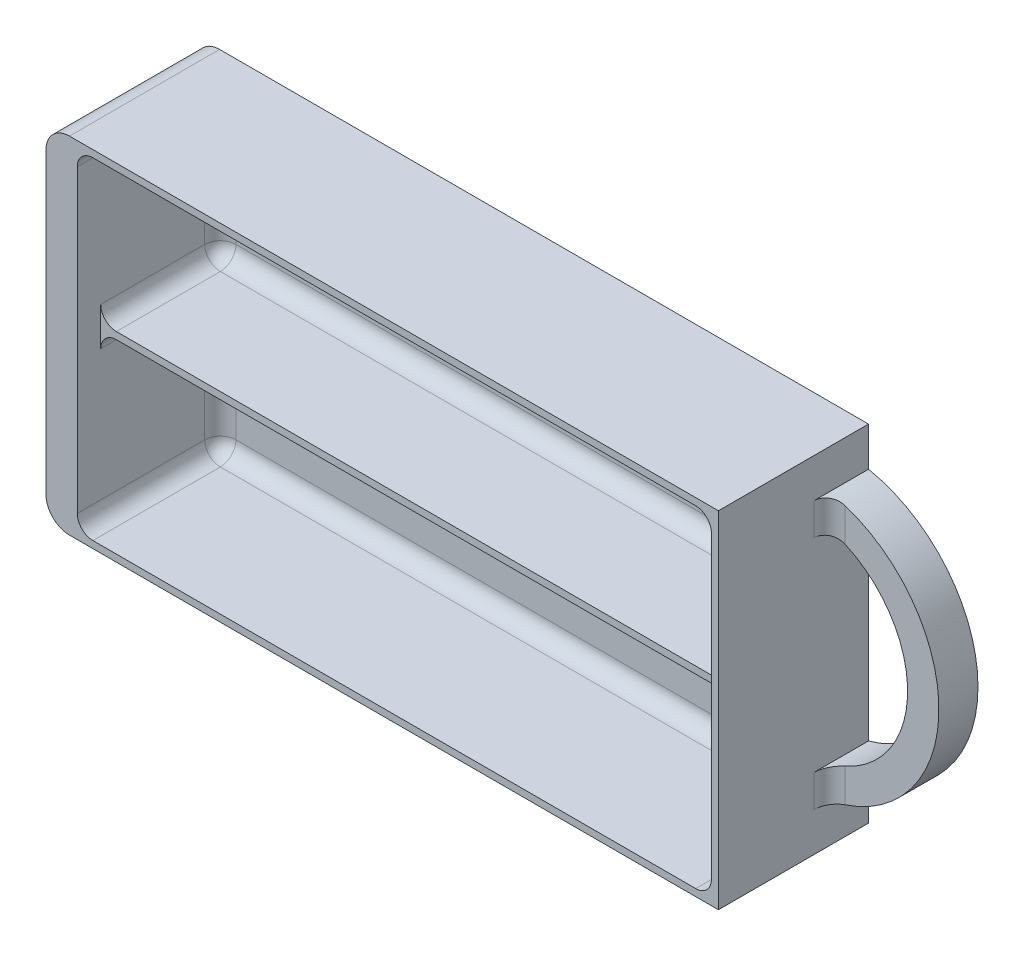
SolidWorks part; units mm, degrees
ref_plane "Спереди" through (0, 0, 0) normal (0, 0, 1) x (1, 0, 0)
ref_plane "Сверху" through (0, 0, 0) normal (0, 1, 0) x (1, 0, 0)
ref_plane "Справа" through (0, 0, 0) normal (1, 0, 0) x (0, 0, -1)
ref_plane "Плоскость4" through (0, 0, 9.6) normal (0, 0, 1) x (1, 0, 0)
sketch "Эскиз1" plane through (0, 0, 9.6) normal (0, 0, 1) x (1, 0, 0)
  line L0 (90, -22.1) -> (90, 22.1)
  line L1 (90, 22.1) -> (4, 22.1)
  line L2 (4, 22.1) -> (4, -22.1)
  line L3 (4, -22.1) -> (90, -22.1)
extrude "Бобышка-Вытянуть1" add sketch "Эскиз1" against normal blind 14.2
sketch "Эскиз2" plane through (0, 0, -4.6) normal (0, 0, -1) x (-1, 0, 0)
  line L0 (-90, -22.1) -> (-90, -17.1)
  line L1 (-90, 17.1) -> (-90, 22.1)
  line L2 (-90, 22.1) -> (-4, 22.1)
  line L3 (-4, 22.1) -> (-4, -22.1)
  line L4 (-4, -22.1) -> (-90, -22.1)
  line L5 (-90, -12.9948) -> (-90, 12.9948)
  arc A0 (-90, -17.1) -> (-90, 17.1) centre (-86.5568, 0) cw
  arc A1 (-90, 12.9948) -> (-90, -12.9948) centre (-86.5568, 0) ccw
extrude "Бобышка-Вытянуть2" add sketch "Эскиз2" along normal blind 5
sketch "Эскиз3" plane through (0, 0, 9.6) normal (0, 0, 1) x (1, 0, 0)
  line L0 (8, -21.2) -> (89.1, -21.2)
  line L1 (89.1, -21.2) -> (89.1, 21.2)
  line L2 (89.1, 21.2) -> (8, 21.2)
  line L3 (8, 21.2) -> (8, -21.2)
extrude "Вырез-Вытянуть1" cut sketch "Эскиз3" against normal blind 18.3
hole_wizard "Диаметр отверстия Ø8.3 (8.3)1" positions "Эскиз5" profile "Эскиз4" hole size "Ø8.3" standard "Ansi Metric"
sketch "Эскиз5" plane through (4, 0, 0) normal (-1, 0, 0) x (0, 0, 1)
  point P0 (0, 0)
sketch "Эскиз4" plane through (4, 0, 0) normal (0, 1, 0) x (0, 0, 1)
  line L0 (0, 0) -> (0, 3.2)
  line L1 (0, 3.2) -> (4.15, 3.2)
  line L2 (4.15, 3.2) -> (4.15, 0)
  line L5 (4.15, 0) -> (0, 0)
  line L10 (0, 3.2) -> (-4.15, 3.2) construction
  line L11 (0, -6.35) -> (0, 107.95) construction
  dimension "Диаметр отверстия" = 8.3
  dimension "Глубина отверстия" = 3.2
  dimension "Угол заточки сверла" = 180
sketch "Эскиз6" plane through (0, 0, 0) normal (0, 1, 0) x (1, 0, 0)
  line L0 (8, -6.6) -> (89.1, -6.6)
rib "Ребро1" sketch "Эскиз6" sketch "Эскиз6" thickness 0.9 extrusion direction parallel to sketch draft on no parameters "D1"=0.9
fillet "Скругление1" radius 3 2 edges at (4, -22.1, 0) (4, 22.1, 0)
sketch "Эскиз7" plane through (4, 0, 0) normal (-1, 0, 0) x (0, 0, 1)
  circle A0 centre (0, 0) radius 4.15 construction
  circle A1 centre (0, 0) radius 4.15
extrude "Бобышка-Вытянуть3" add sketch "Эскиз7" against normal blind 3.5
fillet "Скругление2" radius 2 18 edges at (90, 15.0474, -4.6) (90, -15.0474, -4.6) (8, -21.2, 0.45) (48.55, -21.2, -8.7) (89.1, -21.2, 0.45) (89.1, -10.825, -8.7) (89.1, -0.45, -1.05) (8, -10.825, -8.7) (8, -0.45, -1.05) (48.55, -0.45, -8.7) (89.1, 0.45, -1.05) (89.1, 21.2, 0.45) (89.1, 10.825, -8.7) (48.55, 0.45, -8.7) (8, 10.825, -8.7) (8, 0.45, -1.05) (8, 21.2, 0.45) (48.55, 21.2, -8.7)
